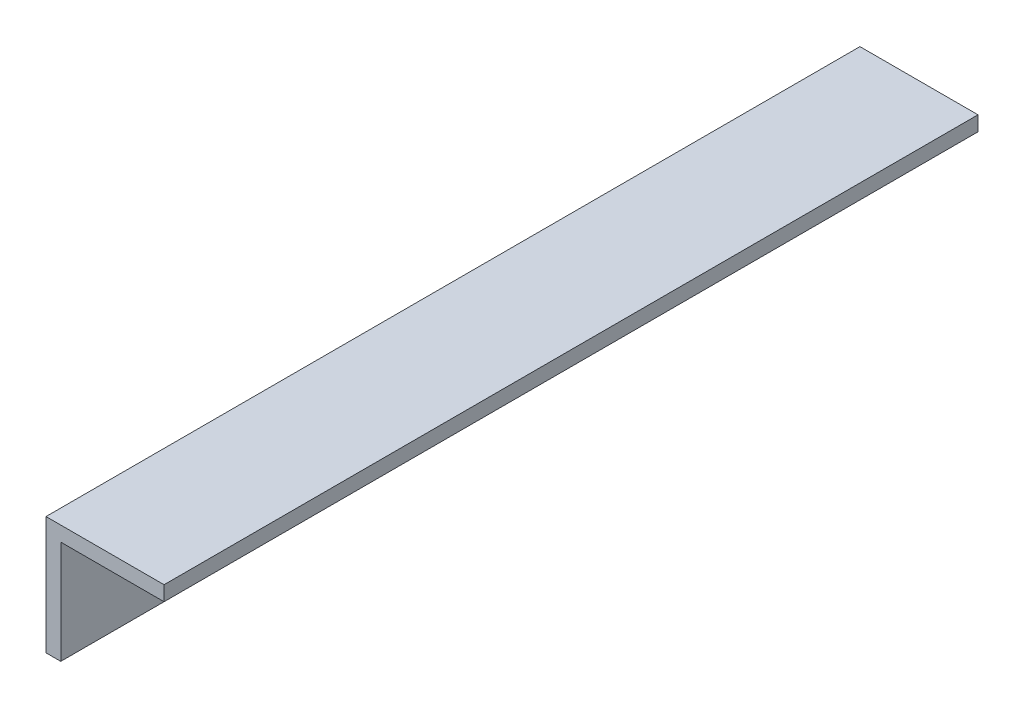
SolidWorks part; units mm, degrees
ref_plane "Front Plane" through (0, 0, 0) normal (0, 0, 1) x (1, 0, 0)
ref_plane "Top Plane" through (0, 0, 0) normal (0, 1, 0) x (1, 0, 0)
ref_plane "Right Plane" through (0, 0, 0) normal (1, 0, 0) x (0, 0, -1)
sketch "Sketch1" plane through (0, 0, 0) normal (0, 0, 1) x (1, 0, 0)
  line L0 (0, 0) -> (0, 25.4)
  line L1 (0, 25.4) -> (25.4, 25.4)
  line L2 (25.4, 25.4) -> (25.4, 22.225)
  line L3 (25.4, 22.225) -> (3.175, 22.225)
  line L4 (3.175, 22.225) -> (3.175, 0)
  line L5 (3.175, 0) -> (0, 0)
  dimension "D1" = 25.4
  dimension "D2" = 25.4
  dimension "D3" = 3.175
  dimension "D4" = 3.175
extrude "Boss-Extrude1" add sketch "Sketch1" along normal blind 175.1
